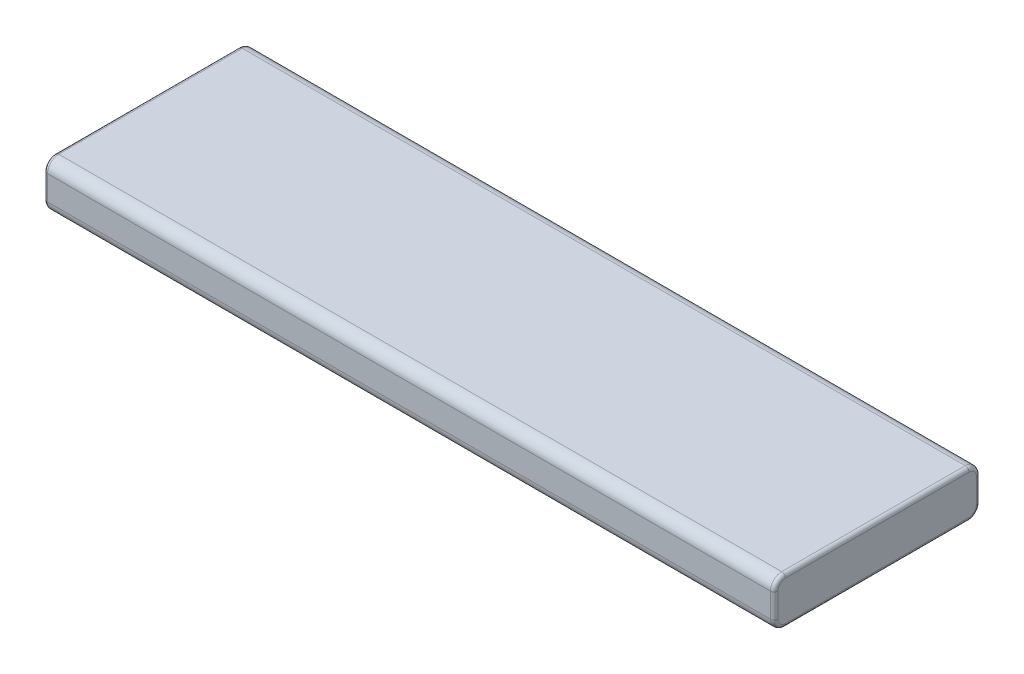
SolidWorks part; units mm, degrees
ref_plane "前视基准面" through (0, 0, 0) normal (0, 0, 1) x (1, 0, 0)
ref_plane "上视基准面" through (0, 0, 0) normal (0, 1, 0) x (1, 0, 0)
ref_plane "右视基准面" through (0, 0, 0) normal (1, 0, 0) x (0, 0, -1)
sketch "草图1" plane through (0, 0, 0) normal (0, 1, 0) x (1, 0, 0)
  line L1 (0, 0) -> (78, 0)
  line L2 (0, 0) -> (0, 22)
  line L3 (0, 22) -> (78, 22)
  line L4 (78, 0) -> (78, 22)
  dimension "D1" = 22
  dimension "D2" = 78
extrude "凸台-拉伸1" add sketch "草图1" along normal blind 5
fillet "圆角1" radius 1.2 4 edges at (39, 0, -22) (39, 5, -22) (39, 0, 0) (39, 5, 0)
fillet "圆角2" radius 0.4 16 edges at (78, 4.6485, -0.3515) (78, 2.5, 0) (78, 0.3515, -0.3515) (78, 0, -11) (78, 0.3515, -21.6485) (78, 2.5, -22) (78, 4.6485, -21.6485) (0, 4.6485, -21.6485) (0, 2.5, -22) (0, 0.3515, -21.6485) (0, 0, -11) (0, 0.3515, -0.3515) (0, 2.5, 0) (0, 4.6485, -0.3515) (78, 5, -11) (0, 5, -11)
